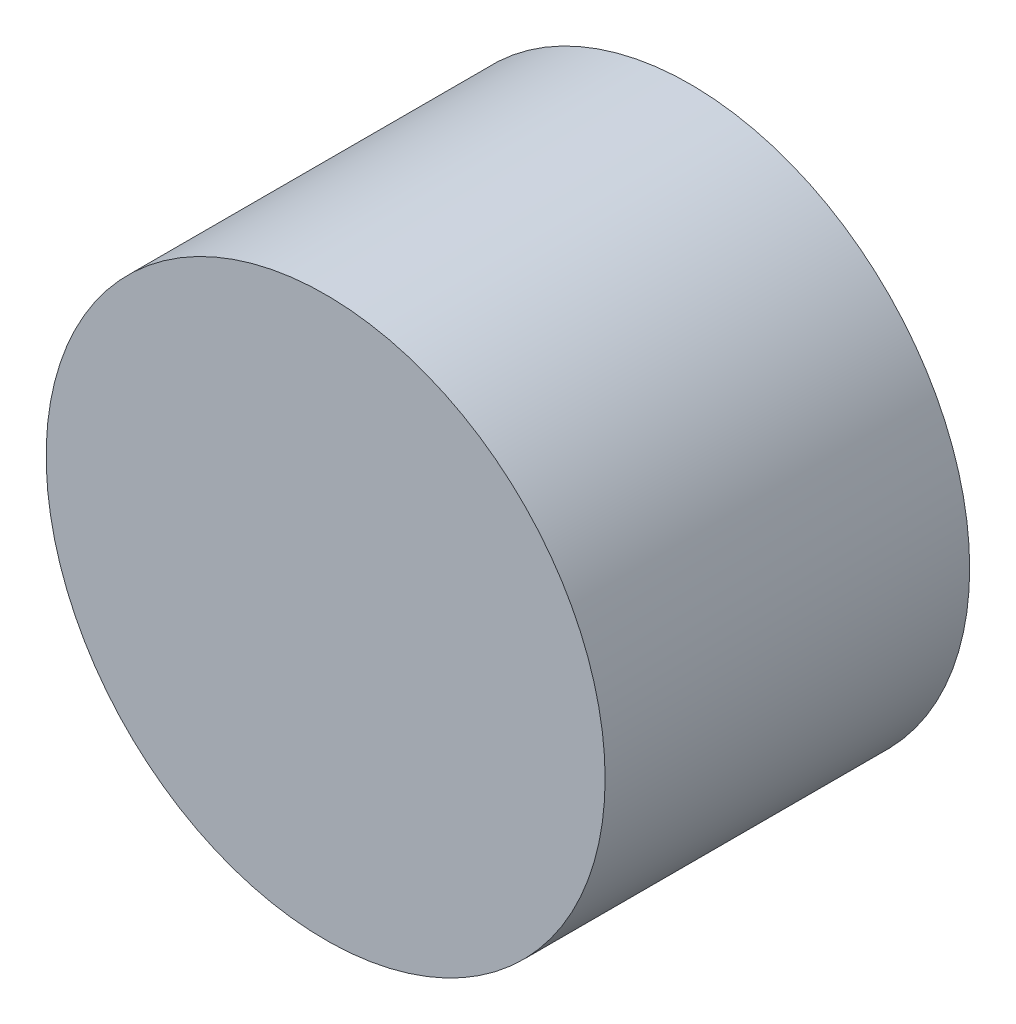
SolidWorks part; units mm, degrees
material "快削黃銅, UNS C36000"
ref_plane "前基準面" through (0, 0, 0) normal (0, 0, 1) x (1, 0, 0)
ref_plane "上基準面" through (0, 0, 0) normal (0, 1, 0) x (1, 0, 0)
ref_plane "右基準面" through (0, 0, 0) normal (1, 0, 0) x (0, 0, -1)
sketch "草圖1" plane through (0, 0, 0) normal (0, 0, 1) x (1, 0, 0)
  circle A0 centre (0, 0) radius 2.3
  dimension "D1" = 4.6
extrude "填料-伸長1" add sketch "草圖1" along normal blind 3
